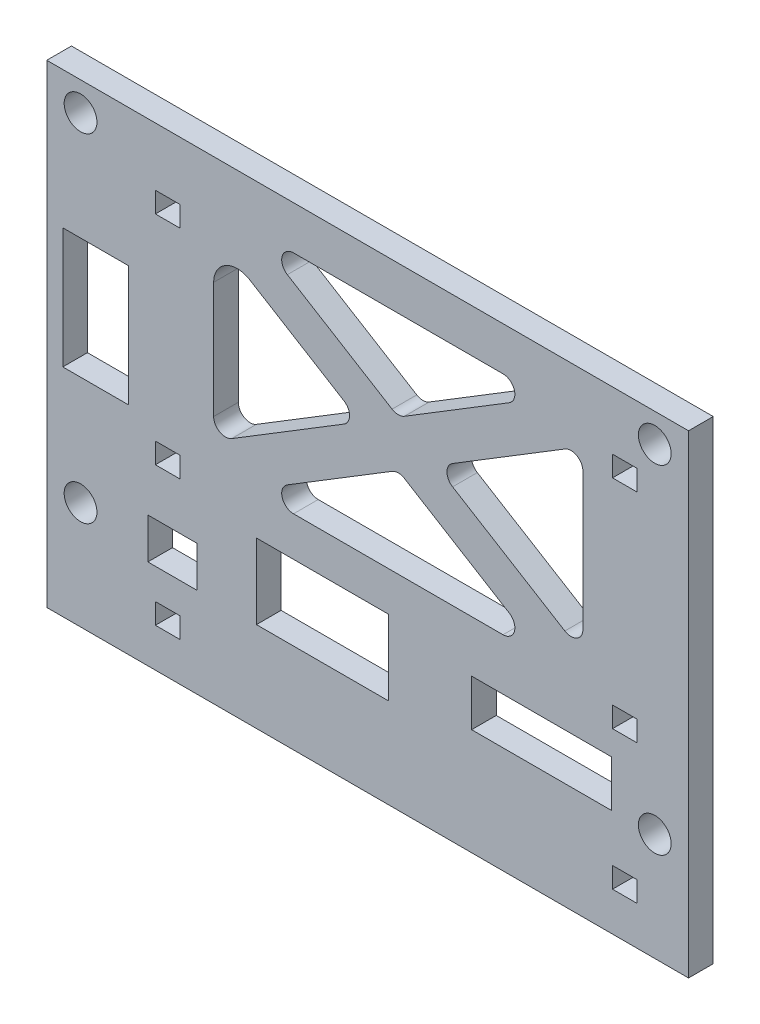
SolidWorks part; units mm, degrees
material "Beech"
ref_plane "Front Plane" through (0, 0, 0) normal (0, 0, 1) x (1, 0, 0)
ref_plane "Top Plane" through (0, 0, 0) normal (0, 1, 0) x (1, 0, 0)
ref_plane "Right Plane" through (0, 0, 0) normal (1, 0, 0) x (0, 0, -1)
sketch "Sketch1" plane through (0, 0, 0) normal (0, 0, 1) x (1, 0, 0)
  line L0 (-20.6375, 0) -> (20.6375, 0)
  line L2 (-20.6375, 0) -> (20.6375, 0)
  line L3 (-20.6375, 0) -> (-20.6375, -5.08)
  line L4 (-20.6375, -5.08) -> (20.6375, -5.08)
  line L5 (20.6375, 0) -> (20.6375, -5.08)
  line L44 (0, 14.605) -> (0, 24.13) construction
  line L46 (-20.6375, 0) -> (-20.6375, 25.4)
  line L47 (-20.6375, 25.4) -> (20.6375, 25.4)
  line L48 (20.6375, 0) -> (20.6375, 25.4)
  line L49 (-20.6375, 12.7) -> (20.6375, 12.7) construction
  circle A2 centre (-18.4658, 23.5585) radius 1.0541
  circle A3 centre (-18.4658, 1.8415) radius 1.0541
  circle A4 centre (18.4658, 1.8415) radius 1.0541
  circle A5 centre (18.4658, 23.5585) radius 1.0541
  point P0 (0, 0)
  point P56 (0, 12.7)
  point P60 (0, 25.4)
  dimension "D14" = 12.7
  dimension "D4" = 2.1082
  dimension "D2" = 5.08
  dimension "D3" = 25.4
  dimension "D12" = 41.275
  dimension "D5" = 2.1717
  dimension "D6" = 1.8415
extrude "Boss-Extrude1" add sketch "Sketch1" along normal blind 1.5875
sketch "Sketch3" plane through (0, 0, 0) normal (0, 0, -1) x (-1, 0, 0)
  line L0 (-15.748, 20.3318) -> (-15.748, 21.6526) construction
  line L1 (-15.748, 21.6526) -> (-17.3355, 21.6526) construction
  line L2 (-17.3355, 21.6526) -> (-17.3355, 20.3318) construction
  line L3 (-17.3355, 20.3318) -> (-15.748, 20.3318) construction
  line L4 (-15.748, 6.3618) -> (-15.748, 7.6826) construction
  line L5 (-15.748, 7.6826) -> (-17.3355, 7.6826) construction
  line L6 (-17.3355, 7.6826) -> (-17.3355, 6.3618) construction
  line L7 (-17.3355, 6.3618) -> (-15.748, 6.3618) construction
  line L8 (-15.748, -2.579) -> (-15.748, -1.2582) construction
  line L9 (-15.748, -1.2582) -> (-17.3355, -1.2582) construction
  line L10 (-17.3355, -1.2582) -> (-17.3355, -2.579) construction
  line L11 (-17.3355, -2.579) -> (-15.748, -2.579) construction
  line L12 (13.6525, 20.3318) -> (13.6525, 21.6526) construction
  line L13 (13.6525, 21.6526) -> (12.065, 21.6526) construction
  line L14 (12.065, 21.6526) -> (12.065, 20.3318) construction
  line L15 (12.065, 20.3318) -> (13.6525, 20.3318) construction
  line L16 (13.6525, 6.3618) -> (13.6525, 7.6826) construction
  line L17 (13.6525, 7.6826) -> (12.065, 7.6826) construction
  line L18 (12.065, 7.6826) -> (12.065, 6.3618) construction
  line L19 (12.065, 6.3618) -> (13.6525, 6.3618) construction
  line L20 (13.6525, -2.579) -> (13.6525, -1.2582) construction
  line L21 (13.6525, -1.2582) -> (12.065, -1.2582) construction
  line L22 (12.065, -1.2582) -> (12.065, -2.579) construction
  line L23 (12.065, -2.579) -> (13.6525, -2.579) construction
  line L24 (-15.748, 20.3318) -> (-15.748, 21.6526)
  line L25 (-15.748, 21.6526) -> (-17.3355, 21.6526)
  line L26 (-17.3355, 21.6526) -> (-17.3355, 20.3318)
  line L27 (-17.3355, 20.3318) -> (-15.748, 20.3318)
  line L28 (-15.748, 6.3618) -> (-15.748, 7.6826)
  line L29 (-15.748, 7.6826) -> (-17.3355, 7.6826)
  line L30 (-17.3355, 7.6826) -> (-17.3355, 6.3618)
  line L31 (-17.3355, 6.3618) -> (-15.748, 6.3618)
  line L32 (-15.748, -2.579) -> (-15.748, -1.2582)
  line L33 (-15.748, -1.2582) -> (-17.3355, -1.2582)
  line L34 (-17.3355, -1.2582) -> (-17.3355, -2.579)
  line L35 (-17.3355, -2.579) -> (-15.748, -2.579)
  line L36 (13.6525, 20.3318) -> (13.6525, 21.6526)
  line L37 (13.6525, 21.6526) -> (12.065, 21.6526)
  line L38 (12.065, 21.6526) -> (12.065, 20.3318)
  line L39 (12.065, 20.3318) -> (13.6525, 20.3318)
  line L40 (13.6525, 6.3618) -> (13.6525, 7.6826)
  line L41 (13.6525, 7.6826) -> (12.065, 7.6826)
  line L42 (12.065, 7.6826) -> (12.065, 6.3618)
  line L43 (12.065, 6.3618) -> (13.6525, 6.3618)
  line L44 (13.6525, -2.579) -> (13.6525, -1.2582)
  line L45 (13.6525, -1.2582) -> (12.065, -1.2582)
  line L46 (12.065, -1.2582) -> (12.065, -2.579)
  line L47 (12.065, -2.579) -> (13.6525, -2.579)
extrude "Attachment Holes" cut sketch "Sketch3" against normal up to next
sketch "Sketch2" plane through (0, 0, 1.5875) normal (0, 0, 1) x (1, 0, 0)
  line L1 (15.748, 20.3318) -> (15.748, 21.6526) construction
  line L2 (-12.065, 21.6526) -> (-12.065, 20.3318) construction
  line L7 (15.6858, 1.7743) -> (15.6858, 4.7602)
  line L8 (15.6858, 4.7602) -> (6.6858, 4.7602)
  line L9 (6.6858, 4.7602) -> (6.6858, 1.7743)
  line L10 (6.6858, 1.7743) -> (15.6858, 1.7743)
  line L11 (15.6858, 1.7743) -> (15.6858, 4.7602)
  line L12 (1.3552, 5.5335) -> (-7.1538, 5.5335)
  line L13 (1.3552, 0.7075) -> (1.3552, 5.5335)
  line L14 (-7.1538, 0.7075) -> (1.3552, 0.7075)
  line L15 (-7.1538, 5.5335) -> (-7.1538, 0.7075)
  line L16 (1.3552, 5.5335) -> (-7.1538, 5.5335)
  line L17 (1.3552, 0.7075) -> (1.3552, 5.5335)
  line L18 (-7.1538, 0.7075) -> (1.3552, 0.7075)
  line L19 (-7.1538, 5.5335) -> (-7.1538, 0.7075)
  line L20 (-10.9638, 3.3237) -> (-14.1388, 3.3237)
  line L21 (-10.9638, 0.7075) -> (-10.9638, 3.3237)
  line L22 (-14.1388, 0.7075) -> (-10.9638, 0.7075)
  line L23 (-14.1388, 3.3237) -> (-14.1388, 0.7075)
  line L24 (-10.9638, 3.3237) -> (-14.1388, 3.3237)
  line L25 (-10.9638, 0.7075) -> (-10.9638, 3.3237)
  line L26 (-14.1388, 0.7075) -> (-10.9638, 0.7075)
  line L27 (-14.1388, 3.3237) -> (-14.1388, 0.7075)
  line L28 (-19.6078, 8.834) -> (-15.3878, 8.834)
  line L29 (-19.6078, 16.584) -> (-19.6078, 8.834)
  line L30 (-15.3878, 16.584) -> (-19.6078, 16.584)
  line L31 (-15.3878, 8.834) -> (-15.3878, 16.584)
  line L32 (-19.6078, 8.834) -> (-15.3878, 8.834)
  line L33 (-19.6078, 16.584) -> (-19.6078, 8.834)
  line L34 (-15.3878, 16.584) -> (-19.6078, 16.584)
  line L35 (-15.3878, 8.834) -> (-15.3878, 16.584)
  line L36 (15.6858, 4.7602) -> (6.6858, 4.7602)
  line L37 (6.6858, 4.7602) -> (6.6858, 1.7743)
  line L38 (6.6858, 1.7743) -> (15.6858, 1.7743)
  line L64 (-9.906, 21.1171) -> (11.4098, 8.0735)
  line L65 (-9.906, 22.606) -> (13.843, 22.606)
  line L66 (-9.906, 22.606) -> (-9.906, 8.0735)
  line L67 (-9.906, 8.0735) -> (13.843, 8.0735)
  line L68 (13.843, 22.606) -> (13.843, 8.0735)
  line L69 (-9.906, 22.606) -> (13.843, 8.0735) construction
  line L70 (-9.906, 8.0735) -> (13.843, 22.606) construction
  line L71 (-7.4728, 22.606) -> (13.843, 9.5624)
  line L72 (-7.4728, 8.0735) -> (13.843, 21.1171)
  line L73 (-9.906, 9.5624) -> (11.4098, 22.606)
  line L74 (-9.2431, 6.9902) -> (14.5059, 21.5227) construction
  line L75 (-10.5689, 9.1568) -> (13.1801, 23.6893) construction
  line L76 (-10.5689, 21.5227) -> (13.1801, 6.9902) construction
  line L77 (-9.2431, 23.6893) -> (14.5059, 9.1568) construction
  line L78 (-20.6375, 25.4) -> (20.6375, 25.4) construction
  point P30 (1.9685, 15.3398)
  dimension "D9" = 2.794
  dimension "D10" = 2.54
  dimension "D11" = 1.905
  dimension "D12" = 2.159
  dimension "D2" = 0
  dimension "D3" = 0
  dimension "D4" = 0
  dimension "D5" = 1.27
  dimension "D6" = 1.27
  dimension "D7" = 1.27
  dimension "D8" = 1.27
  dimension "D13" = 0
extrude "Cut-Extrude1" cut sketch "Sketch2" against normal up to surface (1.5875 mm away) contours L72 L67 L64 | L72 L71 L68 | L71 L73 L65 | L66 L73 L64 | L16 L19 L18 L17 | L32 L35 L34 L33 | L24 L27 L26 L25 | L37 L38 L11 L36
fillet "Fillet8" radius 0.762 11 edges at (-7.4728, 8.0735, 0.7937) (-9.906, 9.5624, 0.7937) (11.4098, 8.0735, 0.7937) (13.843, 9.5624, 0.7937) (13.843, 21.1171, 0.7937) (11.4098, 22.606, 0.7937) (-7.4728, 22.606, 0.7937) (1.9685, 13.8508, 0.7937) (4.4017, 15.3398, 0.7937) (1.9685, 16.8287, 0.7937) (-0.4647, 15.3398, 0.7937)
fillet "Fillet9" radius 1.524 1 edges at (-9.906, 21.1171, 0.7937)
